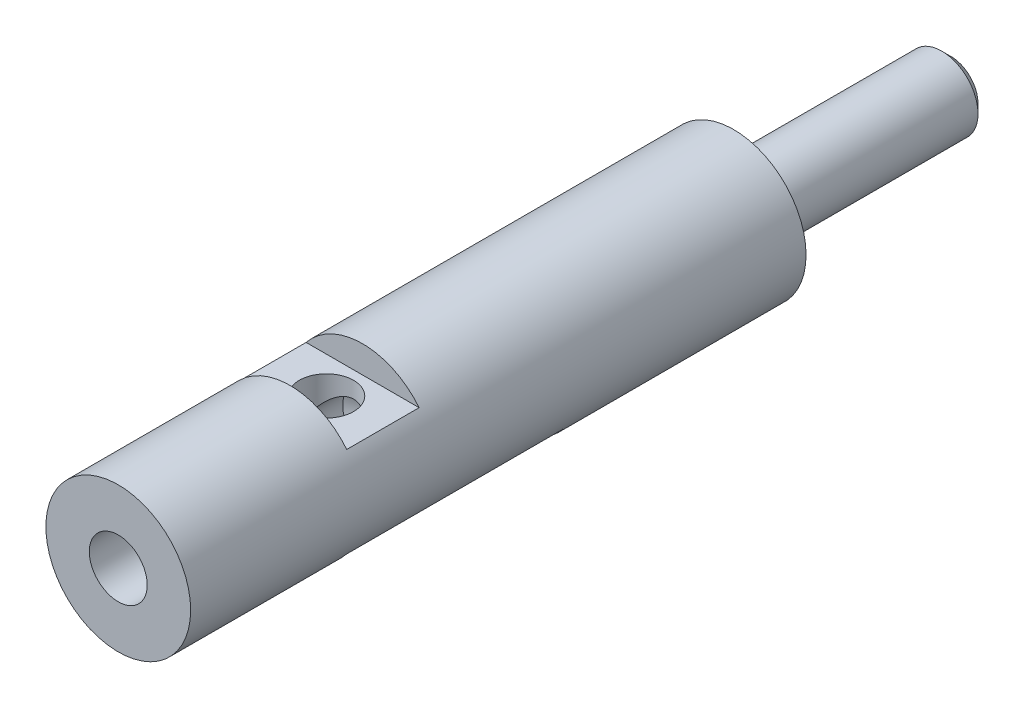
SolidWorks part; units mm, degrees
ref_plane "Front Plane" through (0, 0, 0) normal (0, 0, 1) x (1, 0, 0)
ref_plane "Top Plane" through (0, 0, 0) normal (0, 1, 0) x (1, 0, 0)
ref_plane "Right Plane" through (0, 0, 0) normal (1, 0, 0) x (0, 0, -1)
sketch "Sketch1" plane through (0, 0, 0) normal (0, 0, 1) x (1, 0, 0)
  circle A0 centre (0, 0) radius 4
  dimension "D1" = 8
extrude "Boss-Extrude1" add sketch "Sketch1" against normal blind 34
sketch "Sketch2" plane through (0, 0, -34) normal (0, 0, -1) x (-1, 0, 0)
  circle A0 centre (0, 0) radius 2
  dimension "D1" = 4
extrude "Boss-Extrude2" add sketch "Sketch2" along normal blind 12
chamfer "Chamfer1" distance 0.5 angle 45 1 edges at (-2, 0, -46)
hole_wizard "Ø3.2 (3.2) Diameter Hole1" positions "Sketch4" profile "Sketch3" hole size "Ø3.2" standard "ANSI Metric"
sketch "Sketch4" plane through (0, 0, 0) normal (0, 0, 1) x (1, 0, 0)
  point P0 (0, 0)
sketch "Sketch3" plane through (0, 0, 0) normal (1, 0, 0) x (0, -1, 0)
  line L0 (0, 0) -> (0, 14.9614)
  line L1 (0, 14.9614) -> (1.6, 14)
  line L2 (1.6, 14) -> (1.6, 0)
  line L5 (1.6, 0) -> (0, 0)
  line L10 (0, 14.9614) -> (-1.6, 14) construction
  line L11 (0, -6.35) -> (0, 107.95) construction
  dimension "Hole Dia." = 3.2
  dimension "Hole Depth" = 14
  dimension "Drill Angle" = 118
sketch "Sketch5" plane through (0, 0, 0) normal (1, 0, 0) x (0, 0, -1)
  line L0 (0, -4) -> (34, -4) construction
  line L1 (9.5, -4) -> (21.5, -4)
  line L2 (9.5, -4) -> (9.5, -2.5)
  line L3 (9.5, -2.5) -> (21.5, -2.5)
  line L4 (21.5, -4) -> (21.5, -2.5)
  line L5 (34, 4) -> (0, 4) construction
  line L6 (0, 4) -> (0, -4) construction
  line L7 (9.5, 4) -> (13.5, 4)
  line L8 (9.5, 4) -> (9.5, 2.5)
  line L9 (9.5, 2.5) -> (13.5, 2.5)
  line L10 (13.5, 4) -> (13.5, 2.5)
  dimension "D1" = 1.5
  dimension "D2" = 12
  dimension "D3" = 1.5
  dimension "D4" = 4
  dimension "D5" = 9.5
extrude "Cut-Extrude1" cut sketch "Sketch5" against normal through all and the other way through all
hole_wizard "Ø3.0 (3) Diameter Hole1" positions "Sketch7" profile "Sketch6" hole size "Ø3.0" standard "ANSI Metric"
sketch "Sketch7" plane through (0, 2.5, 0) normal (0, 1, 0) x (1, 0, 0)
  line L0 (-3.1225, 9.5) -> (3.1225, 13.5) construction
  point P7 (0, 11.5)
sketch "Sketch6" plane through (0, 2.5, -11.5) normal (1, 0, 0) x (0, 0, 1)
  line L0 (0, 0) -> (0, 0.9)
  line L1 (0, 0.9) -> (1.5, 0.9)
  line L2 (1.5, 0.9) -> (1.5, 0)
  line L5 (1.5, 0) -> (0, 0)
  line L11 (0, -6.35) -> (0, 107.95) construction
  dimension "Thru Hole Dia." = 3
  dimension "Thru Hole Depth" = 0.9
